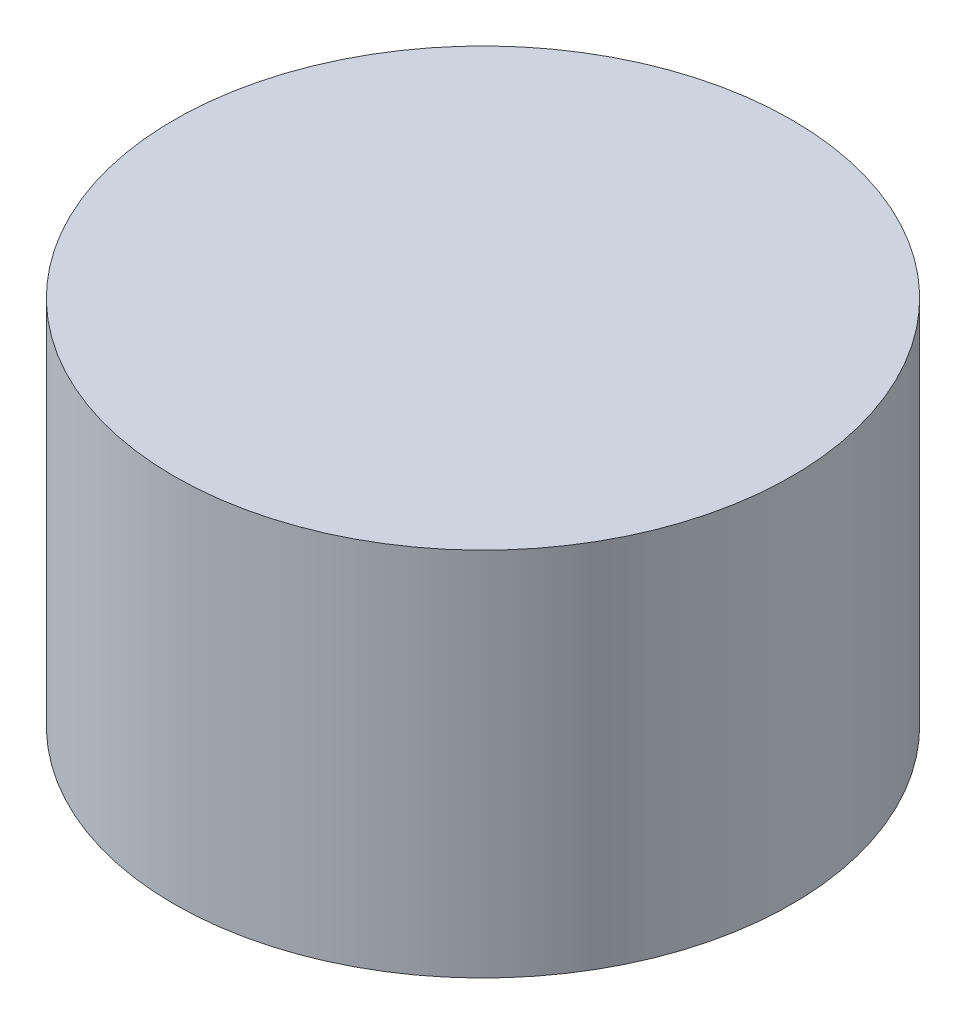
SolidWorks part; units mm, degrees
ref_plane "Ebene vorne" through (0, 0, 0) normal (0, 0, 1) x (1, 0, 0)
ref_plane "Ebene oben" through (0, 0, 0) normal (0, 1, 0) x (1, 0, 0)
ref_plane "Ebene rechts" through (0, 0, 0) normal (1, 0, 0) x (0, 0, -1)
sketch "Skizze2" plane through (0, 0, 0) normal (0, 1, 0) x (1, 0, 0)
  circle A0 centre (0, 0) radius 250
  dimension "D1" = 500
extrude "Aufsatz-Linear austragen1" add sketch "Skizze2" along normal blind 300
